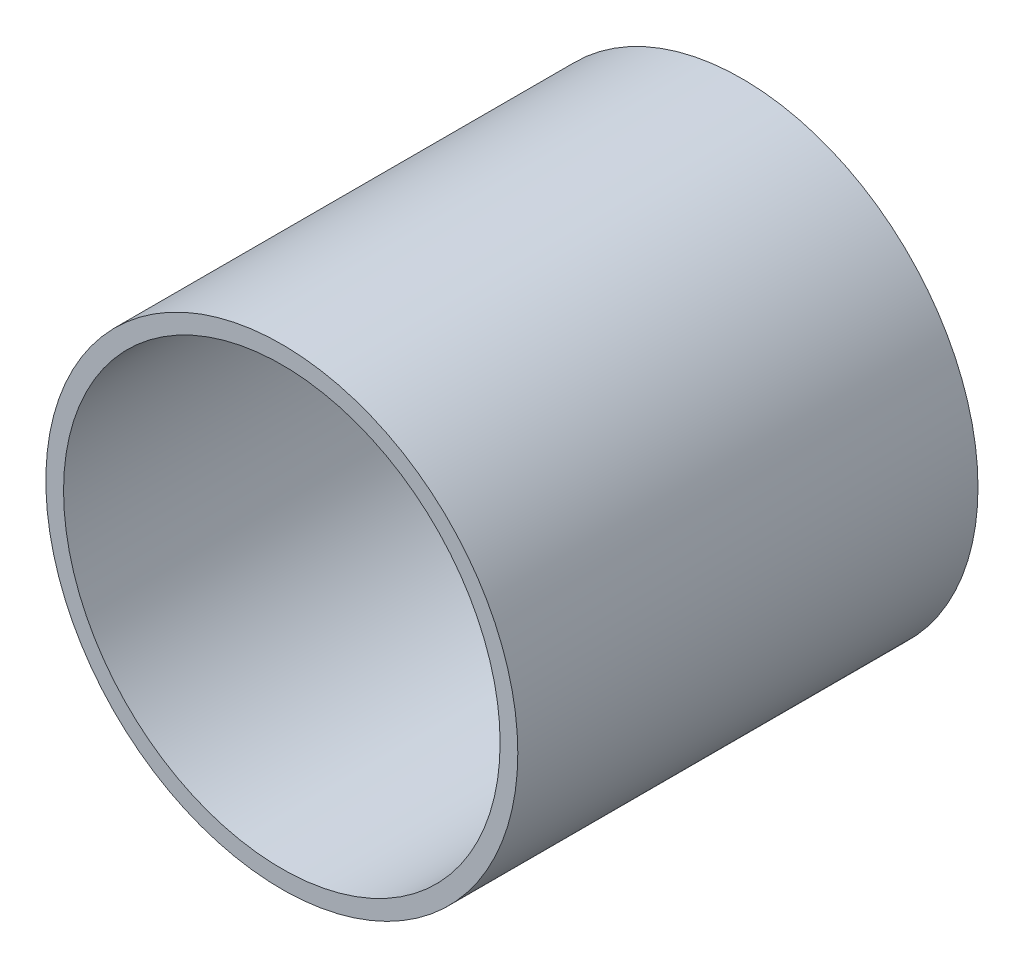
SolidWorks part; units mm, degrees
ref_plane "Front Plane" through (0, 0, 0) normal (0, 0, 1) x (1, 0, 0)
ref_plane "Top Plane" through (0, 0, 0) normal (0, 1, 0) x (1, 0, 0)
ref_plane "Right Plane" through (0, 0, 0) normal (1, 0, 0) x (0, 0, -1)
sketch "Sketch1" plane through (0, 0, 0) normal (0, 0, 1) x (1, 0, 0)
  circle A0 centre (0, 0) radius 37
  circle A1 centre (0, 0) radius 40
  dimension "D1" = 80
  dimension "D2" = 74
extrude "Boss-Extrude1" add sketch "Sketch1" along normal blind 78
